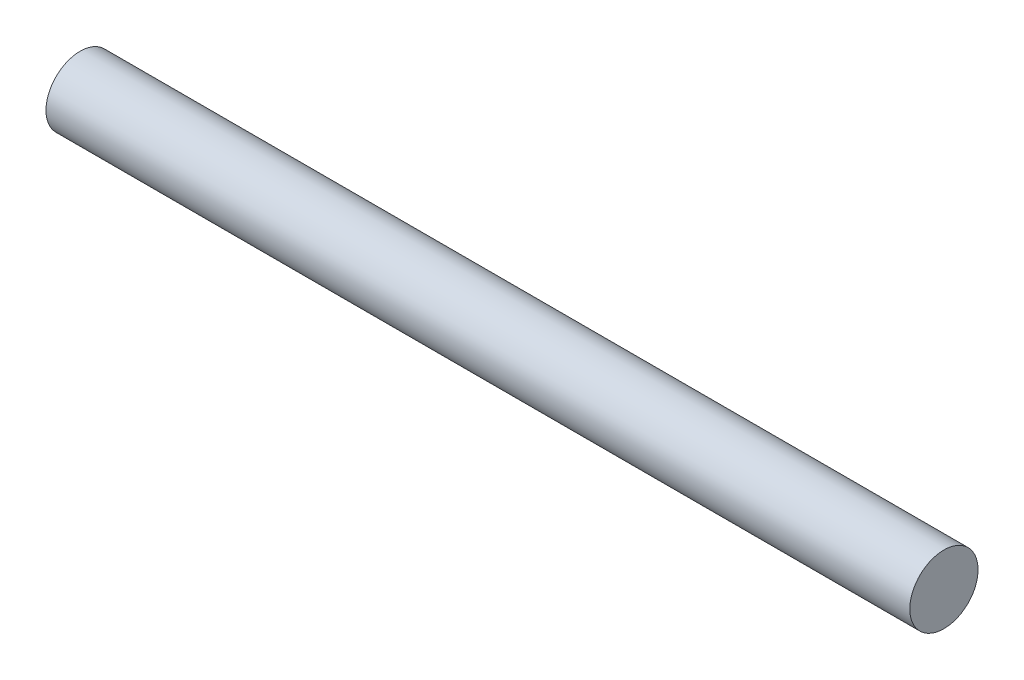
SolidWorks part; units mm, degrees
material "Aluminium"
ref_plane "Ebene vorne" through (0, 0, 0) normal (1, 0, 0) x (0, 1, 0)
ref_plane "Ebene oben" through (0, 0, 0) normal (0, 0, 1) x (0, 1, 0)
ref_plane "Ebene rechts" through (0, 0, 0) normal (0, 1, 0) x (-1, 0, 0)
sketch "Skizze1" plane through (0, 0, 0) normal (1, 0, 0) x (0, 1, 0)
  circle A0 centre (0, 0) radius 3.675
  dimension "D1" = 7.35
extrude "Aufsatz-Linear austragen1" add sketch "Skizze1" along normal blind 93
sketch "Skizze3" plane through (0, 0, 0) normal (-1, 0, 0) x (0, -1, 0)
  circle A0 centre (0, 0) radius 4.25
  dimension "D1" = 8.5
